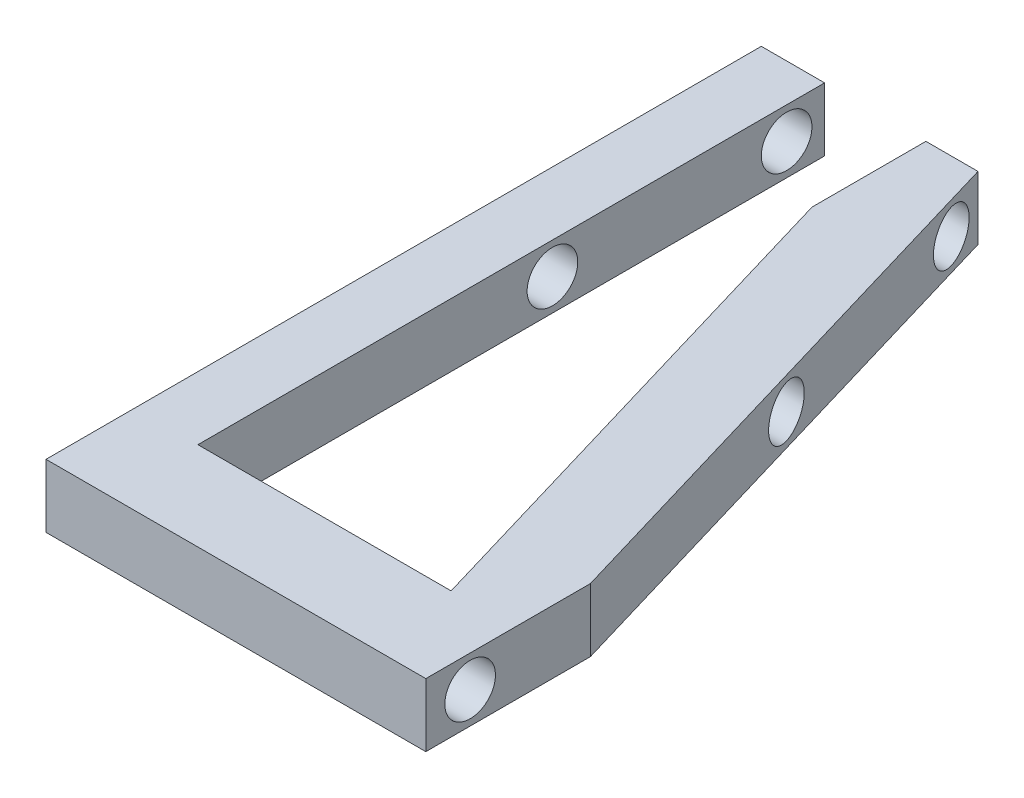
SolidWorks part; units mm, degrees
ref_plane "Plan de face" through (0, 0, 0) normal (0, 0, 1) x (1, 0, 0)
ref_plane "Plan de dessus" through (0, 0, 0) normal (0, 1, 0) x (1, 0, 0)
ref_plane "Plan de droite" through (0, 0, 0) normal (1, 0, 0) x (0, 0, -1)
sketch "Sketch1" plane through (0, 0, 0) normal (0, 1, 0) x (1, 0, 0)
  line L0 (-9.9991, 49.5) -> (-14.9991, 49.5)
  line L1 (-14.9991, 49.5) -> (-14.9991, -7)
  line L2 (-14.9991, -7) -> (15.0009, -7)
  line L3 (15.0009, -7) -> (15.0009, 6)
  line L4 (15.0009, 6) -> (2.1157, 49.5)
  line L5 (2.1157, 49.5) -> (-1.9991, 49.5)
  line L6 (-1.9991, 49.5) -> (-1.9991, 40.505)
  line L7 (-1.9991, 40.505) -> (9.9991, 0)
  line L8 (9.9991, 0) -> (-9.9991, 0)
  line L9 (-9.9991, 0) -> (-9.9991, 49.5)
  point P2 (1.3116, 46.8677)
  point P11 (0, 0)
  dimension "D1" = 5
  dimension "D2" = 6.5
  dimension "D3" = 7
  dimension "D4" = 30
  dimension "D5" = 13
  dimension "D6" = 56.5
  dimension "D7" = 8
  dimension "D8" = 16.5
extrude "Boss-Extrude1" add sketch "Sketch1" along normal mid plane 5
sketch "Sketch2" plane through (-14.9991, 0, 0) normal (-1, 0, 0) x (0, 0, 1)
  line L0 (-49.5, 0) -> (7, 0) construction
  line L1 (-49.5, 2.5) -> (-49.5, -2.5) construction
  line L2 (7, 2.5) -> (7, -2.5) construction
  circle A0 centre (-46.5, 0) radius 2
  circle A1 centre (-28, 0) radius 2
  circle A2 centre (3.5, 0) radius 2
  dimension "D1" = 4
  dimension "D2" = 4
  dimension "D3" = 4
  dimension "D4" = 3
  dimension "D5" = 31.5
  dimension "D6" = 3.5
extrude "Cut-Extrude1" cut sketch "Sketch2" against normal up to surface (30 mm away) up to face at (15.0009, 0, 0.5)
